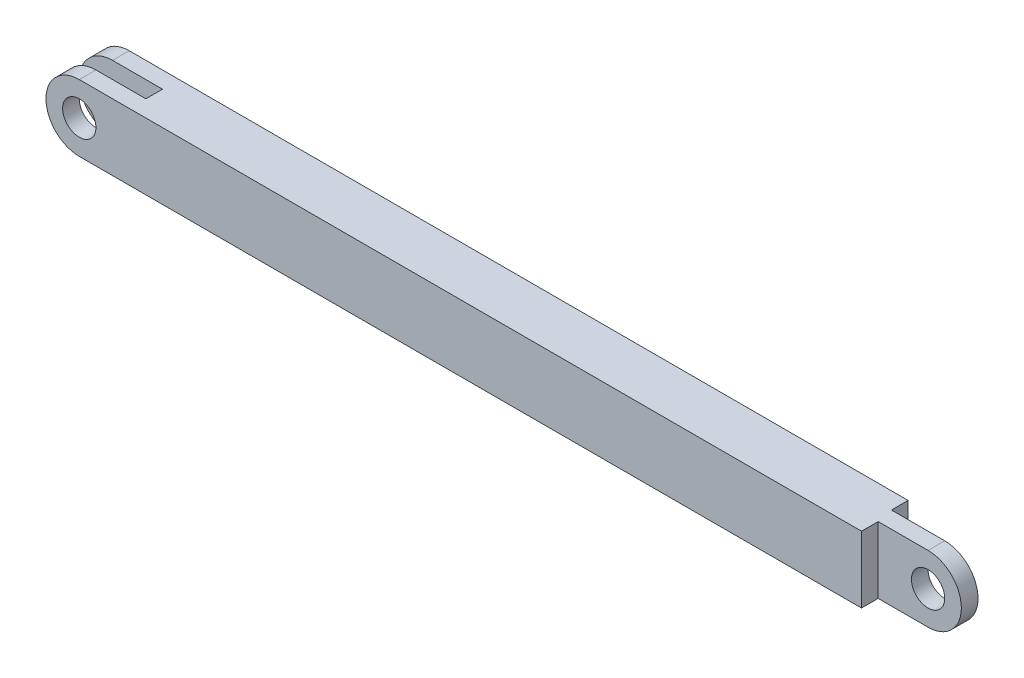
SolidWorks part; units mm, degrees
ref_plane "Front Plane" through (0, 0, 0) normal (0, 0, 1) x (1, 0, 0)
ref_plane "Top Plane" through (0, 0, 0) normal (0, 1, 0) x (1, 0, 0)
ref_plane "Right Plane" through (0, 0, 0) normal (1, 0, 0) x (0, 0, -1)
sketch "Sketch1" plane through (0, 0, 0) normal (0, 0, 1) x (1, 0, 0)
  line L0 (0, 0) -> (500, 0) construction
  line L1 (0, 20) -> (500, 20)
  line L2 (0, -20) -> (500, -20)
  arc A0 (0, 20) -> (0, -20) centre (0, 0) ccw
  arc A1 (500, -20) -> (500, 20) centre (500, 0) ccw
  circle A2 centre (0, 0) radius 10
  circle A3 centre (500, 0) radius 10
  point P3 (250, 0)
  dimension "D2" = 20
  dimension "D1" = 500
extrude "Boss-Extrude1" add sketch "Sketch1" along normal blind 30
sketch "Sketch4" plane through (0, -20, 0) normal (0, -1, 0) x (1, 0, 0)
  line L0 (-20, 30) -> (-20, 0) construction
  line L1 (30, 20) -> (-39.9301, 20)
  line L2 (30, 20) -> (30, 10)
  line L3 (30, 10) -> (-39.9301, 10)
  line L4 (-39.9301, 20) -> (-39.9301, 10)
  line L5 (0, 0) -> (500, 0) construction
  line L8 (470, 47.163) -> (470, 20)
  line L9 (470, 20) -> (535.2908, 20)
  line L10 (535.2908, 20) -> (535.2908, 10)
  line L11 (535.2908, 10) -> (467.9908, 10)
  line L12 (467.9908, 10) -> (467.9908, -15.7955)
  line L13 (467.9908, -15.7955) -> (553.1534, -15.7955)
  line L14 (553.1534, -15.7955) -> (553.1534, 47.163)
  line L15 (553.1534, 47.163) -> (470, 47.163)
  line L16 (520, 0) -> (520, 30) construction
  dimension "D1" = 50
  dimension "D2" = 10
  dimension "D3" = 10
  dimension "D4" = 50
  dimension "D5" = 10
  dimension "D6" = 10
extrude "Cut-Extrude1" cut sketch "Sketch4" against normal through all
